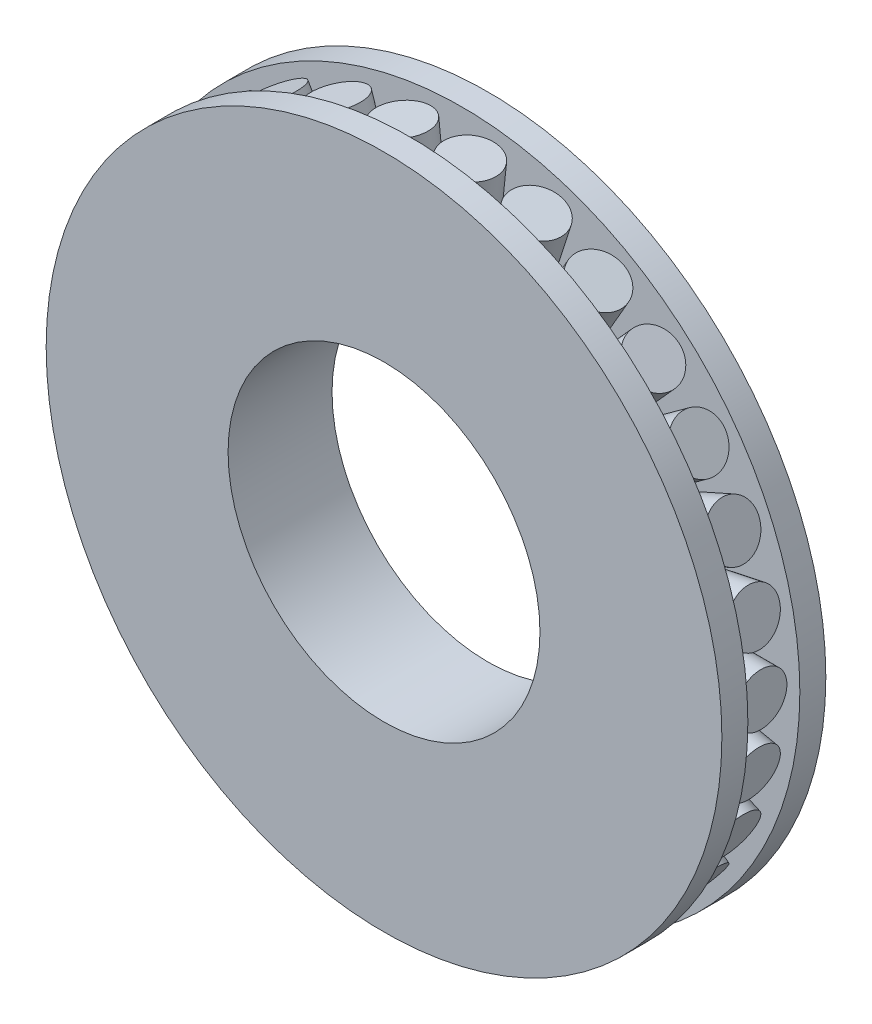
SolidWorks part; units mm, degrees
ref_plane "前视基准面" through (0, 0, 0) normal (0, 0, 1) x (1, 0, 0)
ref_plane "上视基准面" through (0, 0, 0) normal (0, 1, 0) x (1, 0, 0)
ref_plane "右视基准面" through (0, 0, 0) normal (1, 0, 0) x (0, 0, -1)
sketch "草图1" plane through (0, 0, 0) normal (0, 0, 1) x (1, 0, 0)
  circle A0 centre (0, 0) radius 6
  circle A1 centre (0, 0) radius 13
  dimension "D1" = 26
  dimension "D2" = 12
extrude "凸台-拉伸1" add sketch "草图1" along normal blind 4
ref_plane "基准面1" through (0, 0, 2) normal (0, 0, -1) x (-1, 0, 0)
sketch "草图2" plane through (0, 0, 2) normal (0, 0, -1) x (-1, 0, 0)
  circle A0 centre (0, 0) radius 13
  circle A1 centre (0, 0) radius 8
extrude "切除-拉伸1" cut sketch "草图2" against normal blind 1 and the other way blind 1
sketch "草图3" plane through (0, 0, 0) normal (1, 0, 0) x (0, 0, -1)
  line L0 (0, 0) -> (-4, 0) construction
  line L1 (-4, 13) -> (-4, -13) construction
ref_plane "基准面2" through (11, 0, 0) normal (1, 0, 0) x (0, 0, -1)
sketch "草图4" plane through (11, 0, 0) normal (1, 0, 0) x (0, 0, -1)
  line L0 (0, 0) -> (-4, 0) construction
  circle A0 centre (-2, 0) radius 1.0019
extrude "凸台-拉伸4" add sketch "草图4" along normal blind 1.5 and the other way blind 3 separate body
pattern_circular "阵列(圆周)2" count 30 over 360 about axis through (0, 0, 0) along (0, 0, 1) of bodies 109
